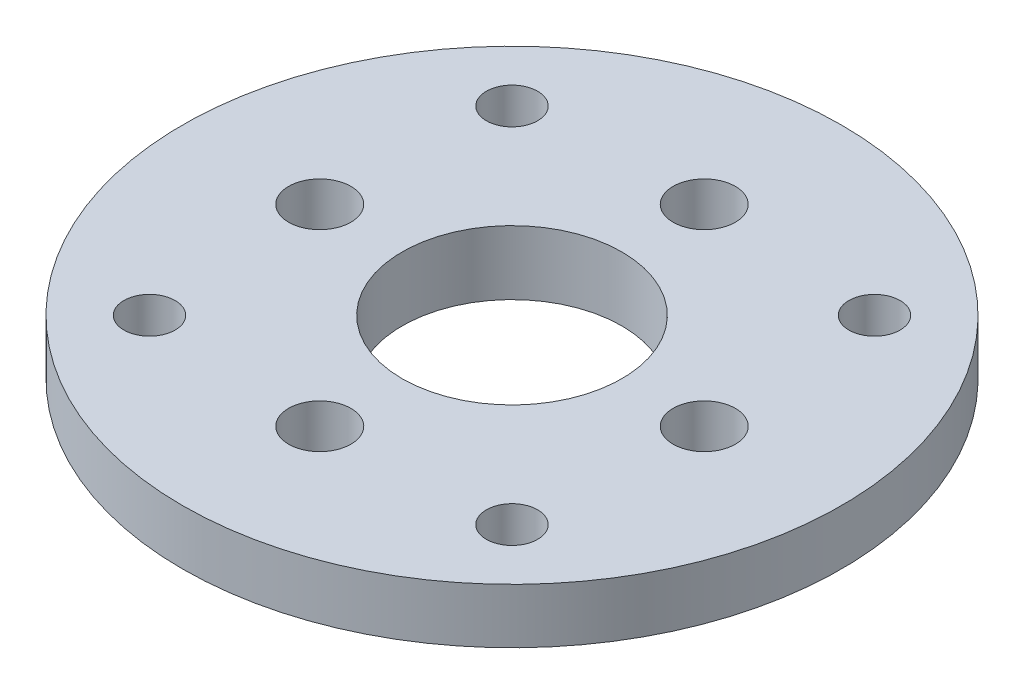
SolidWorks part; units mm, degrees
ref_plane "Front Plane" through (0, 0, 0) normal (0, 0, 1) x (1, 0, 0)
ref_plane "Top Plane" through (0, 0, 0) normal (0, 1, 0) x (1, 0, 0)
ref_plane "Right Plane" through (0, 0, 0) normal (1, 0, 0) x (0, 0, -1)
sketch "Sketch1" plane through (0, 0, 0) normal (0, 1, 0) x (1, 0, 0)
  circle A0 centre (0, 0) radius 16.5
  dimension "D1" = 33
extrude "Boss-Extrude1" add sketch "Sketch1" along normal blind 0.5
sketch "Sketch2" plane through (0, 0.5, 0) normal (0, 1, 0) x (1, 0, 0)
  circle A0 centre (0, 0) radius 18
  dimension "D1" = 36
extrude "Boss-Extrude2" add sketch "Sketch2" along normal blind 3
sketch "Sketch3" plane through (0, 0, 0) normal (0, 1, 0) x (1, 0, 0)
  circle A0 centre (0, 0) radius 6
  dimension "D1" = 12
extrude "Cut-Extrude1" cut sketch "Sketch3" along normal through all
sketch "Sketch4" plane through (0, 0, 0) normal (0, 1, 0) x (1, 0, 0)
  line L0 (-1.925, 0) -> (1.925, 0) construction
  circle A0 centre (10.5, 0) radius 1.7
  dimension "D2" = 3.4
  dimension "D1" = 10.5
extrude "Cut-Extrude2" cut sketch "Sketch4" along normal through all
pattern_circular "CirPattern1" count 4 over 360 about axis through (0, 0, 0) along (0, 1, 0) of "Cut-Extrude2"
sketch "Sketch5" plane through (0, 0, 0) normal (0, 1, 0) x (1, 0, 0)
  line L0 (0, 0) -> (20.333, 0) construction
  line L1 (0, 0) -> (16.7478, 16.7478) construction
  circle A0 centre (9.8995, 9.8995) radius 1.4
  dimension "D3" = 2.8
  dimension "D1" = 45
  dimension "D2" = 14
extrude "Cut-Extrude3" cut sketch "Sketch5" along normal through all
pattern_circular "CirPattern2" count 4 over 360 about axis through (0, 0, 0) along (0, 1, 0) of "Cut-Extrude3"
equation "\"pin_circle_R\" = 27"
equation "\"ecc\" = 1.5"
equation "\"n_pins\" = 11"
equation "\"pin_d\" = 3"
equation "\"out_pin_R\" = 18.5"
equation "\"disc_clr\" = 0.1"
equation "\"seat_6803\" = 26.1"
equation "\"disc_t\" = 5"
equation "\"out_hole_clr\" = 0.5"
equation "\"boss_17\" = 17.15"
equation "\"rotor_bolt_R\" = 10"
equation "\"m25_clr\" = 2.8"
equation "\"m25_head\" = 5"
equation "\"insert_hole\" = 4.4"
equation "\"csk\" = 0.6"
equation "\"peg_d\" = 3.0"
equation "\"plug_d\" = 8.6"
equation "\"peg_clr\" = 0.3"
equation "\"m3_clr\" = 3.4"
equation "\"m3_head\" = 6.2"
equation "\"pin_press\" = 3.2"
equation "\"hub_30\" = 30.25"
equation "\"hub_short\" = 0.2"
equation "\"m3_tap\" = 2.8"
equation "\"D2@Sketch4\"=\"m3_clr\""
equation "\"D3@Sketch5\"=\"m3_tap\""
equation "\"seat_6806\" = 42.1"
equation "\"pin_slip\" = 3.3"
equation "\"rear_plate_t\" = 2"
